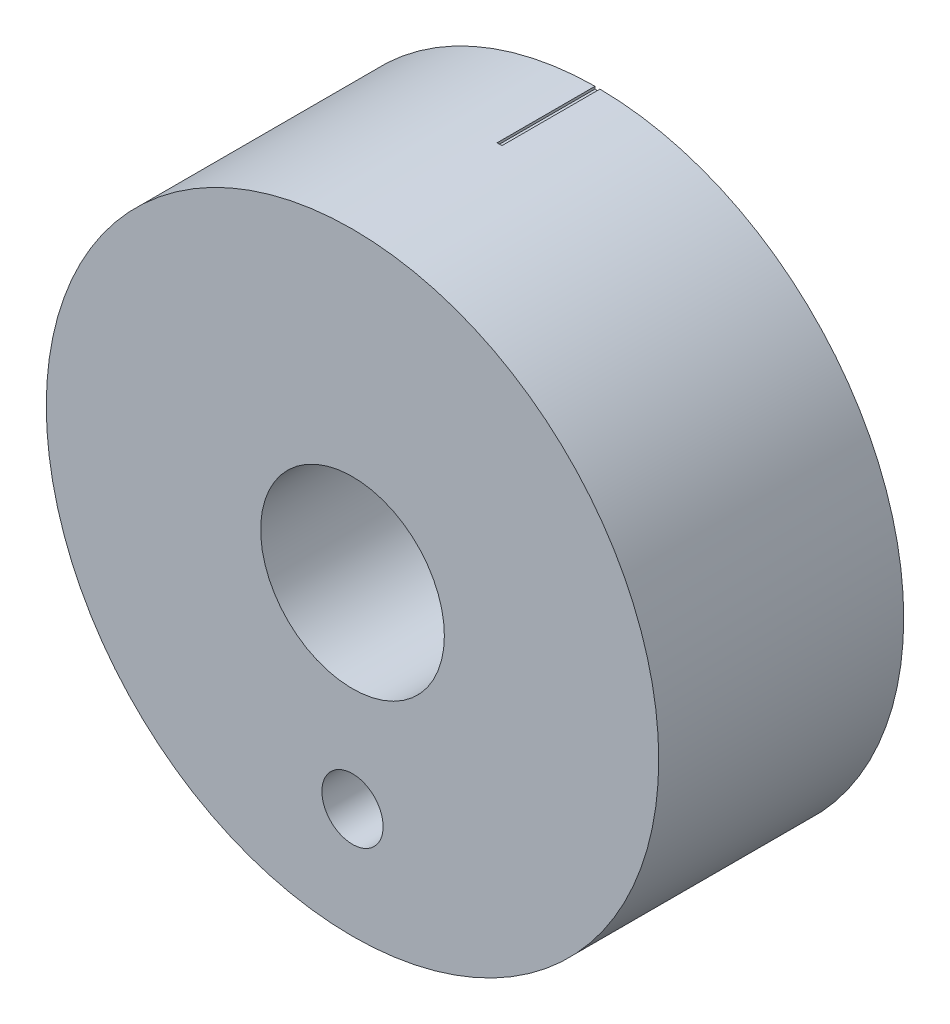
SolidWorks part; units mm, degrees
material "6061-T6 (SS)"
ref_plane "Front Plane" through (0, 0, 0) normal (0, 0, 1) x (1, 0, 0)
ref_plane "Top Plane" through (0, 0, 0) normal (0, 1, 0) x (1, 0, 0)
ref_plane "Right Plane" through (0, 0, 0) normal (1, 0, 0) x (0, 0, -1)
sketch "Sketch1" plane through (0, 0, 0) normal (0, 0, 1) x (1, 0, 0)
  circle A0 centre (0, 0) radius 15.875
  circle A1 centre (0, 0) radius 4.7625
  dimension "D1" = 31.75
  dimension "D2" = 9.525
extrude "Boss-Extrude1" add sketch "Sketch1" against normal blind 12.7
sketch "Sketch3" plane through (0, 0, -12.7) normal (0, 0, 1) x (1, 0, 0)
  line L0 (0, 0) -> (0, 15.875) construction
  line L2 (-0.127, 15.748) -> (0.127, 15.748)
  line L3 (-0.127, 15.748) -> (-0.127, 15.875)
  line L4 (-0.127, 15.875) -> (0.127, 15.875)
  line L5 (0.127, 15.748) -> (0.127, 15.875)
  circle A0 centre (0, 0) radius 15.875 construction
  dimension "D1" = 0.254
  dimension "D2" = 0.127
extrude ".001 line Cut-Extrude1" cut sketch "Sketch3" along normal blind 5.08
pattern_circular ".001 lines CirPattern1" [suppressed] count 100 over 360
sketch "Sketch5" plane through (0, 0, -7.62) normal (0, 0, -1) x (-1, 0, 0)
  line L3 (-0.127, 15.8745) -> (-0.127, 15.748)
  line L4 (0.127, 15.748) -> (0.127, 15.8745)
  line L5 (-0.127, 15.748) -> (0.127, 15.748)
  line L6 (-0.127, 15.8745) -> (-0.127, 15.748)
  line L7 (0.127, 15.748) -> (0.127, 15.8745)
  line L8 (-0.127, 15.748) -> (0.127, 15.748)
  arc A1 (0.127, 15.8745) -> (-0.127, 15.8745) centre (0, 0) ccw
  arc A2 (0.127, 15.8745) -> (-0.127, 15.8745) centre (0, 0) ccw
  dimension "D1" = 0
extrude ".01 line Cut-Extrude3" [suppressed] cut sketch "Sketch5" against normal blind 2.54
pattern_circular ".01 line CirPattern2" [suppressed] count 10 over 360
sketch "Sketch6" [suppressed] plane through (0, 0, -7.62) normal (0, 0, -1) x (-1, 0, 0)
  line L3 (-5.0263, 15.0583) -> (-4.9872, 14.938)
  line L4 (-4.7456, 15.0165) -> (-4.7847, 15.1368)
  line L5 (-4.9872, 14.938) -> (-4.7456, 15.0165)
  line L6 (-5.0263, 15.0583) -> (-4.9872, 14.938)
  line L7 (-4.7456, 15.0165) -> (-4.7847, 15.1368)
  line L8 (-4.9872, 14.938) -> (-4.7456, 15.0165)
  arc A1 (-4.7847, 15.1368) -> (-5.0263, 15.0583) centre (0, 0) ccw
  arc A2 (-4.7847, 15.1368) -> (-5.0263, 15.0583) centre (0, 0) ccw
  dimension "D1" = 0
extrude ".005 line Cut-Extrude4" [suppressed] cut sketch "Sketch6" against normal blind 1.27
pattern_circular "CirPattern3" [suppressed] count 10 over 360
sketch "Sketch7" plane through (0, 0, 0) normal (0, 1, 0) x (1, 0, 0)
  line L0 (-1.143, 0.762) -> (98.6026, 0.762) construction
  line L1 (-15.875, 0) -> (15.875, 0) construction
  line L2 (-1.143, 0.762) -> (8.763, 0.762) construction
  text T0 "1"
  text T1 "2"
  text T2 "3"
  text T3 "4"
  text T4 "5"
  text T5 "6"
  text T6 "7"
  text T7 "8"
  text T8 "9"
  text T9 "0"
  point P5 (-1.143, 0.762)
  point P8 (8.763, 0.762)
  point P9 (18.669, 0.762)
  point P10 (28.575, 0.762)
  point P11 (38.481, 0.762)
  point P12 (48.387, 0.762)
  point P13 (58.293, 0.762)
  point P14 (68.199, 0.762)
  point P15 (78.105, 0.762)
  point P16 (88.011, 0.762)
  dimension "D1" = 0.762
  dimension "D2" = 99.7456
  dimension "D4" = 9.906
  dimension "D5" = 1.143
  dimension "D3" = 10
wrap "Wrap1" [suppressed] sketch "Sketch7" source sketch "Sketch7" thickness 0.254 parameters "D1"=0.254
hole_wizard "1/8 (0.1250) Dowel Hole1" positions "Sketch9" profile "Sketch8" hole size "1/8" standard "ANSI Inch" end condition through all
sketch "Sketch9" plane through (0, 0, -12.7) normal (0, 0, -1) x (-1, 0, 0)
  line L0 (0, 0) -> (0, -10.16) construction
  point P0 (0, -10.16)
  dimension "D1" = 10.16
sketch "Sketch8" plane through (0, -10.16, -12.7) normal (1, 0, 0) x (0, 1, 0)
  line L0 (0, 0) -> (0, 12.7)
  line L1 (0, 12.7) -> (1.5875, 12.7)
  line L2 (1.5875, 12.7) -> (1.5875, 0)
  line L5 (1.5875, 0) -> (0, 0)
  line L11 (0, -6.35) -> (0, 107.95) construction
  dimension "Thru Hole Dia." = 3.175
  dimension "Thru Hole Depth" = 12.7
equation "\"dovetail-angle\" = 55"
equation "\"dovetail-stock-width\" = 5"
equation "\"dovetail-stock-height\" = 1.25"
equation "\"dovetail-depth\" = 0.5 * \"dovetail-stock-height\""
equation "\"dovetail-throat-width\" = \"dovetail-stock-width\" - (2 * \"dovetail-depth\")"
equation "\"delta-x\" = 6"
equation "\"delta-y\" = 3"
equation "\"gib-thickness\" = 0.25"
equation "\"x-slide-length\" = \"dovetail-stock-width\" + \"delta-x\""
equation "\"y-slide-length\" = \"dovetail-stock-width\" + \"delta-y\""
equation "\"dog-point-diam\" = .149"
equation "\"dog-point-length\" = .067"
equation "\"dovetail-double-height\" = 2 * \"dovetail-depth\" + 0.5"
equation "\"acme-major-diam\" = .5"
equation "\"acme-pitch-diam\" = 0.45"
equation "\"acme-minor-diam\" = 0.4"
equation "\"acme-nut-od\" = 1.47"
equation "\"acme-nut-length\" = 1"
equation "\"acme-nut-trim-height\" = .75"
equation "\"screw-bearing-od\" = 0.5"
equation "\"screw-bearing-length\" = .25"
equation "\"screw-bearing-id\" = .375"
equation "\"end-plate-thickness\" = \"screw-bearing-length\""
equation "\"screw-add-length\" = 2 * \"end-plate-thickness\" + 1 + 0.5"
equation "\"x-screw-length\" = \"x-slide-length\" + \"screw-add-length\""
equation "\"y-screw-length\" = \"y-slide-length\" + \"screw-add-length\""
equation "\"acme-nut-mount-hole-space-horz\" = 0.82"
equation "\"acme-nut-mount-hole-space-vert\" = 0.5 * \"acme-nut-length\""
equation "\"vise-hole-center-dist\" = 6.75"
equation "\"wiper_plate_clearance\" = .03"
equation "\"D2@Sketch1\"=\"screw-bearing-id\""
equation "\"dial-width\" = 0.5"
equation "\"D1@Boss-Extrude1\"=\"dial-width\""
